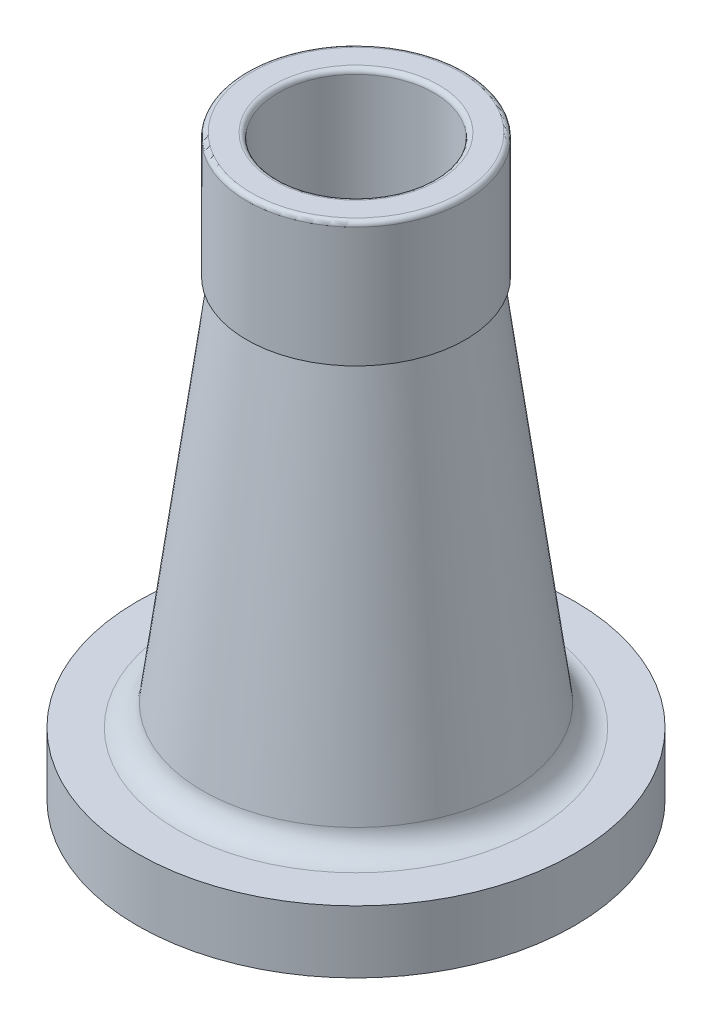
SolidWorks part; units mm, degrees
material "Gray Cast Iron"
ref_plane "Front Plane" through (0, 0, 0) normal (0, 0, 1) x (1, 0, 0)
ref_plane "Top Plane" through (0, 0, 0) normal (0, 1, 0) x (1, 0, 0)
ref_plane "Right Plane" through (0, 0, 0) normal (1, 0, 0) x (0, 0, -1)
sketch "Sketch2" plane through (0, 0, 0) normal (0, 0, 1) x (1, 0, 0)
  line L0 (0, 0) -> (0, 185) construction
  line L1 (0, 0) -> (70, 0) construction
  line L2 (70, 0) -> (70, 20)
  line L3 (70, 20) -> (57.0134, 20)
  line L4 (49.0822, 26.9531) -> (33.5, 145)
  line L5 (33.5, 145) -> (35, 145)
  line L6 (35, 145) -> (35, 183.5)
  line L7 (33.5, 185) -> (26.5, 185)
  line L8 (25, 183.5) -> (25, 132.9792)
  line L10 (42.1573, 3) -> (47, 3)
  line L12 (50, 0) -> (70, 0)
  line L13 (42.1573, 3) -> (25, 132.9792)
  line L14 (39.4275, 23.6799) -> (23.586, 143.6914) construction
  line L15 (49.3415, 24.9886) -> (33.5, 145) construction
  arc A1 (57.0134, 20) -> (49.0822, 26.9531) centre (57.0134, 28) cw
  arc A2 (47, 3) -> (50, 0) centre (47, 0) cw
  arc A3 (26.5, 185) -> (25, 183.5) centre (26.5, 183.5) ccw
  arc A4 (35, 183.5) -> (33.5, 185) centre (33.5, 183.5) ccw
  point P18 (50, 3)
  point P21 (50, 20)
  point P26 (35, 185)
  point P27 (0, 0)
  dimension "D10" = 50
  dimension "D12" = 8
  dimension "D13" = 3
  dimension "D14" = 1.5
  dimension "D15" = 1.5
  dimension "D1" = 185
  dimension "D2" = 70
  dimension "D3" = 20
  dimension "D4" = 50
  dimension "D5" = 3
  dimension "D6" = 40
  dimension "D7" = 33.5
  dimension "D8" = 25
  dimension "D9" = 35
  dimension "D11" = 10
revolve "01_Body" add sketch "Sketch2" angle 360 about L0
